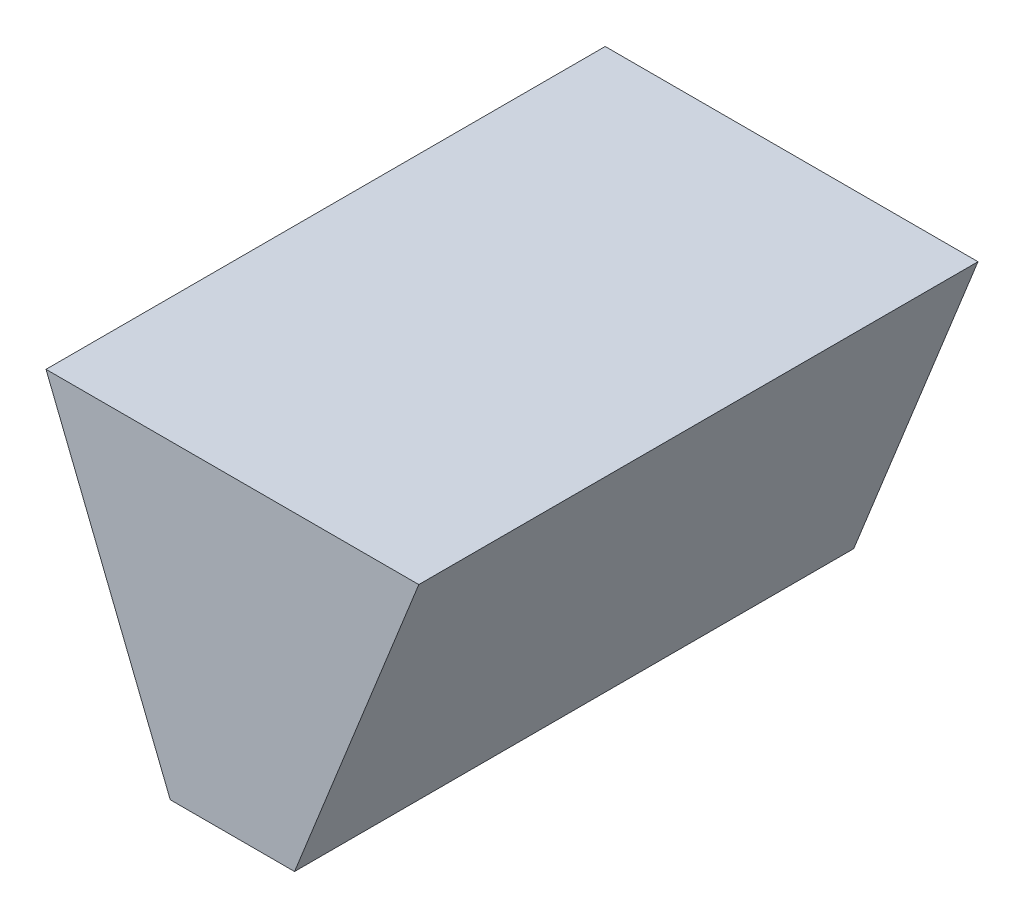
SolidWorks part; units mm, degrees
ref_plane "Front Plane" through (0, 0, 0) normal (0, 0, 1) x (1, 0, 0)
ref_plane "Top Plane" through (0, 0, 0) normal (0, 1, 0) x (1, 0, 0)
ref_plane "Right Plane" through (0, 0, 0) normal (1, 0, 0) x (0, 0, -1)
sketch "Sketch1" plane through (0, 0, 0) normal (0, 0, 1) x (1, 0, 0)
  line L0 (0, 0) -> (0, 50)
  line L1 (0, 50) -> (-30, 50)
  line L2 (-30, 50) -> (-10, 0)
  line L3 (-10, 0) -> (0, 0)
  dimension "D1" = 10
  dimension "D2" = 50
  dimension "D3" = 30
extrude "Boss-Extrude1" add sketch "Sketch1" along normal blind 90
mirror "Mirror1" about plane through (0, 0, 0) normal (1, 0, 0) of bodies 101
